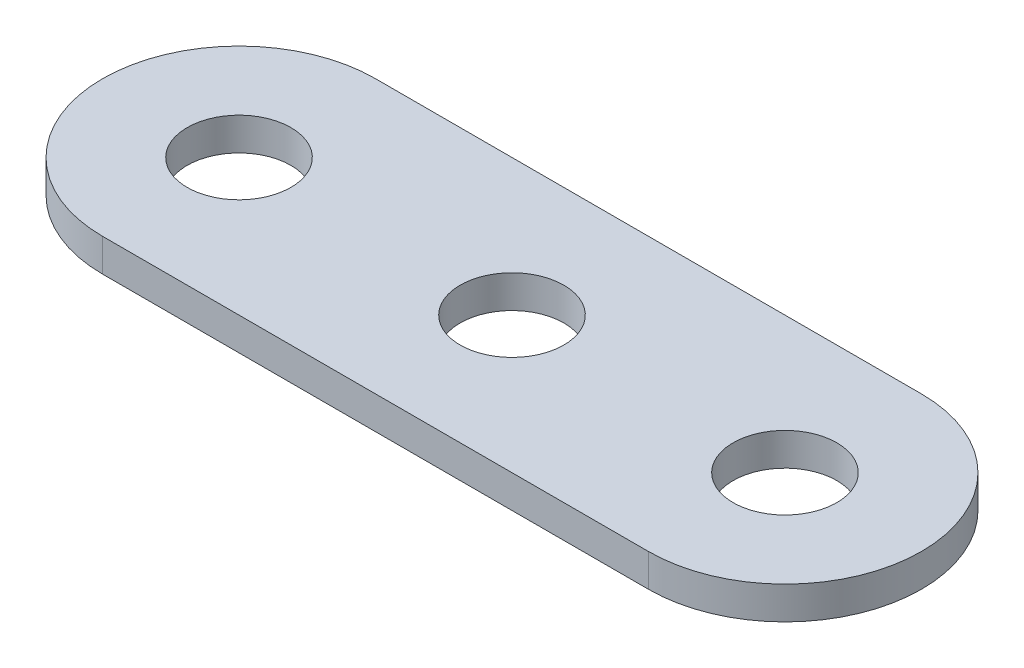
SolidWorks part; units mm, degrees
material "1060 Alloy"
ref_plane "Front Plane" through (0, 0, 0) normal (0, 0, 1) x (1, 0, 0)
ref_plane "Top Plane" through (0, 0, 0) normal (0, 1, 0) x (1, 0, 0)
ref_plane "Right Plane" through (0, 0, 0) normal (1, 0, 0) x (0, 0, -1)
sketch "Sketch1" plane through (0, 0, 0) normal (0, 1, 0) x (1, 0, 0)
  line L0 (0, 0) -> (-25.4, 0) construction
  line L1 (0, 6.35) -> (-25.4, 6.35)
  line L2 (0, -6.35) -> (-25.4, -6.35)
  line L3 (-25.4, 0) -> (-12.7, 0) construction
  arc A0 (0, -6.35) -> (0, 6.35) centre (0, 0) ccw
  arc A1 (-25.4, 6.35) -> (-25.4, -6.35) centre (-25.4, 0) ccw
  circle A2 centre (-25.4, 0) radius 2.413
  circle A3 centre (-12.7, 0) radius 2.413
  circle A4 centre (0, 0) radius 2.413
  dimension "D1" = 12.7
  dimension "D3" = 4.826
  dimension "D4" = 3
  dimension "D2" = 25.4
  dimension "D5" = 12.7
extrude "Boss-Extrude1" add sketch "Sketch1" along normal blind 1.524
